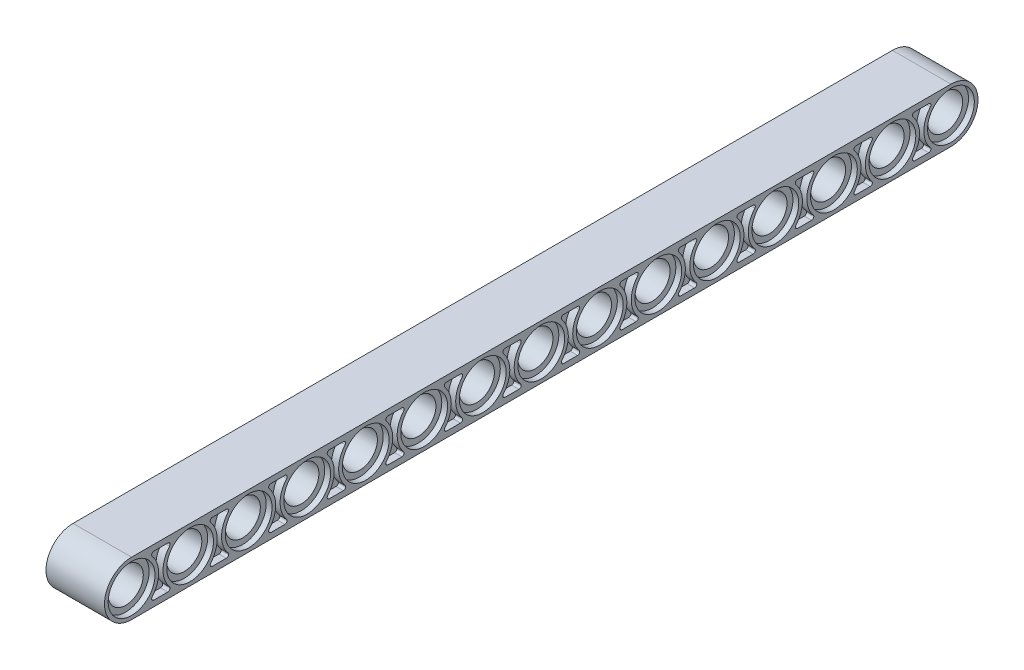
SolidWorks part; units mm, degrees
ref_plane "Front Plane" through (0, 0, 0) normal (0, 0, 1) x (1, 0, 0)
ref_plane "Top Plane" through (0, 0, 0) normal (0, 1, 0) x (1, 0, 0)
ref_plane "Right Plane" through (0, 0, 0) normal (1, 0, 0) x (0, 0, -1)
sketch "Sketch1" plane through (0, 0, 0) normal (1, 0, 0) x (0, 0, -1)
  line L0 (-29.185, 0) -> (82.815, 0) construction
  line L1 (-29.185, 3.7) -> (82.815, 3.7)
  line L2 (-29.185, -3.7) -> (82.815, -3.7)
  arc A0 (-29.185, 3.7) -> (-29.185, -3.7) centre (-29.185, 0) ccw
  arc A1 (82.815, -3.7) -> (82.815, 3.7) centre (82.815, 0) ccw
  circle A2 centre (-29.185, 0) radius 2.4
  circle A3 centre (-21.185, 0) radius 2.4
  circle A4 centre (-13.185, 0) radius 2.4
  circle A5 centre (-5.185, 0) radius 2.4
  circle A6 centre (2.815, 0) radius 2.4
  circle A7 centre (10.815, 0) radius 2.4
  circle A8 centre (18.815, 0) radius 2.4
  circle A9 centre (26.815, 0) radius 2.4
  circle A10 centre (34.815, 0) radius 2.4
  circle A11 centre (42.815, 0) radius 2.4
  circle A12 centre (50.815, 0) radius 2.4
  circle A13 centre (58.815, 0) radius 2.4
  circle A14 centre (66.815, 0) radius 2.4
  circle A15 centre (74.815, 0) radius 2.4
  circle A16 centre (82.815, 0) radius 2.4
  point P3 (26.815, 0)
  dimension "D3" = 15
  dimension "D1" = 7.4
  dimension "D2" = 112
extrude "Boss-Extrude1" add sketch "Sketch1" along normal blind 8
sketch "Sketch2" plane through (8, 0, 0) normal (1, 0, 0) x (0, 0, -1)
  line L0 (-26.1453, 2.9) -> (-24.2248, 2.9)
  line L1 (82.815, 3.7) -> (-29.185, 3.7) construction
  line L2 (-29.185, 0) -> (-21.185, 0) construction
  line L3 (-26.1453, -2.9) -> (-24.2248, -2.9)
  line L4 (-18.1453, 2.9) -> (-16.2248, 2.9)
  line L5 (-18.1453, -2.9) -> (-16.2248, -2.9)
  line L6 (-21.185, 0) -> (-13.185, 0) construction
  line L7 (-10.1453, 2.9) -> (-8.2248, 2.9)
  line L8 (-10.1453, -2.9) -> (-8.2248, -2.9)
  line L9 (-13.185, 0) -> (-5.185, 0) construction
  line L10 (-2.1453, 2.9) -> (-0.2248, 2.9)
  line L11 (-2.1453, -2.9) -> (-0.2248, -2.9)
  line L12 (-5.185, 0) -> (2.815, 0) construction
  line L13 (5.8547, 2.9) -> (7.7752, 2.9)
  line L14 (5.8547, -2.9) -> (7.7752, -2.9)
  line L15 (2.815, 0) -> (10.815, 0) construction
  line L16 (13.8547, 2.9) -> (15.7752, 2.9)
  line L17 (13.8547, -2.9) -> (15.7752, -2.9)
  line L18 (10.815, 0) -> (18.815, 0) construction
  line L19 (21.8547, 2.9) -> (23.7752, 2.9)
  line L20 (21.8547, -2.9) -> (23.7752, -2.9)
  line L21 (18.815, 0) -> (26.815, 0) construction
  line L22 (29.8547, 2.9) -> (31.7752, 2.9)
  line L23 (29.8547, -2.9) -> (31.7752, -2.9)
  line L24 (26.815, 0) -> (34.815, 0) construction
  line L25 (37.8547, 2.9) -> (39.7752, 2.9)
  line L26 (37.8547, -2.9) -> (39.7752, -2.9)
  line L27 (34.815, 0) -> (42.815, 0) construction
  line L28 (45.8547, 2.9) -> (47.7752, 2.9)
  line L29 (45.8547, -2.9) -> (47.7752, -2.9)
  line L30 (42.815, 0) -> (50.815, 0) construction
  line L31 (53.8547, 2.9) -> (55.7752, 2.9)
  line L32 (53.8547, -2.9) -> (55.7752, -2.9)
  line L33 (50.815, 0) -> (58.815, 0) construction
  line L34 (61.8547, 2.9) -> (63.7752, 2.9)
  line L35 (61.8547, -2.9) -> (63.7752, -2.9)
  line L36 (58.815, 0) -> (66.815, 0) construction
  line L37 (69.8547, 2.9) -> (71.7752, 2.9)
  line L38 (69.8547, -2.9) -> (71.7752, -2.9)
  line L39 (66.815, 0) -> (74.815, 0) construction
  line L40 (77.8547, 2.9) -> (79.7752, 2.9)
  line L41 (77.8547, -2.9) -> (79.7752, -2.9)
  line L42 (74.815, 0) -> (82.815, 0) construction
  arc A0 (-26.3733, -2.405) -> (-26.3733, 2.405) centre (-29.185, 0) ccw
  arc A1 (-23.9968, 2.405) -> (-23.9968, -2.405) centre (-21.185, 0) ccw
  arc A2 (-26.3733, -2.405) -> (-26.1453, -2.9) centre (-26.1453, -2.6) ccw
  arc A3 (-23.9968, -2.405) -> (-24.2248, -2.9) centre (-24.2248, -2.6) cw
  arc A4 (-23.9968, 2.405) -> (-24.2248, 2.9) centre (-24.2248, 2.6) ccw
  arc A5 (-26.3733, 2.405) -> (-26.1453, 2.9) centre (-26.1453, 2.6) cw
  arc A6 (-18.3733, -2.405) -> (-18.3733, 2.405) centre (-21.185, 0) ccw
  arc A7 (-15.9968, 2.405) -> (-15.9968, -2.405) centre (-13.185, 0) ccw
  arc A8 (-18.3733, -2.405) -> (-18.1453, -2.9) centre (-18.1453, -2.6) ccw
  arc A9 (-15.9968, -2.405) -> (-16.2248, -2.9) centre (-16.2248, -2.6) cw
  arc A10 (-15.9968, 2.405) -> (-16.2248, 2.9) centre (-16.2248, 2.6) ccw
  arc A11 (-18.3733, 2.405) -> (-18.1453, 2.9) centre (-18.1453, 2.6) cw
  arc A12 (-10.3733, -2.405) -> (-10.3733, 2.405) centre (-13.185, 0) ccw
  arc A13 (-7.9968, 2.405) -> (-7.9968, -2.405) centre (-5.185, 0) ccw
  arc A14 (-10.3733, -2.405) -> (-10.1453, -2.9) centre (-10.1453, -2.6) ccw
  arc A15 (-7.9968, -2.405) -> (-8.2248, -2.9) centre (-8.2248, -2.6) cw
  arc A16 (-7.9968, 2.405) -> (-8.2248, 2.9) centre (-8.2248, 2.6) ccw
  arc A17 (-10.3733, 2.405) -> (-10.1453, 2.9) centre (-10.1453, 2.6) cw
  arc A18 (-2.3733, -2.405) -> (-2.3733, 2.405) centre (-5.185, 0) ccw
  arc A19 (0.0032, 2.405) -> (0.0032, -2.405) centre (2.815, 0) ccw
  arc A20 (-2.3733, -2.405) -> (-2.1453, -2.9) centre (-2.1453, -2.6) ccw
  arc A21 (0.0032, -2.405) -> (-0.2248, -2.9) centre (-0.2248, -2.6) cw
  arc A22 (0.0032, 2.405) -> (-0.2248, 2.9) centre (-0.2248, 2.6) ccw
  arc A23 (-2.3733, 2.405) -> (-2.1453, 2.9) centre (-2.1453, 2.6) cw
  arc A24 (5.6267, -2.405) -> (5.6267, 2.405) centre (2.815, 0) ccw
  arc A25 (8.0032, 2.405) -> (8.0032, -2.405) centre (10.815, 0) ccw
  arc A26 (5.6267, -2.405) -> (5.8547, -2.9) centre (5.8547, -2.6) ccw
  arc A27 (8.0032, -2.405) -> (7.7752, -2.9) centre (7.7752, -2.6) cw
  arc A28 (8.0032, 2.405) -> (7.7752, 2.9) centre (7.7752, 2.6) ccw
  arc A29 (5.6267, 2.405) -> (5.8547, 2.9) centre (5.8547, 2.6) cw
  arc A30 (13.6267, -2.405) -> (13.6267, 2.405) centre (10.815, 0) ccw
  arc A31 (16.0032, 2.405) -> (16.0032, -2.405) centre (18.815, 0) ccw
  arc A32 (13.6267, -2.405) -> (13.8547, -2.9) centre (13.8547, -2.6) ccw
  arc A33 (16.0032, -2.405) -> (15.7752, -2.9) centre (15.7752, -2.6) cw
  arc A34 (16.0032, 2.405) -> (15.7752, 2.9) centre (15.7752, 2.6) ccw
  arc A35 (13.6267, 2.405) -> (13.8547, 2.9) centre (13.8547, 2.6) cw
  arc A36 (21.6267, -2.405) -> (21.6267, 2.405) centre (18.815, 0) ccw
  arc A37 (24.0032, 2.405) -> (24.0032, -2.405) centre (26.815, 0) ccw
  arc A38 (21.6267, -2.405) -> (21.8547, -2.9) centre (21.8547, -2.6) ccw
  arc A39 (24.0032, -2.405) -> (23.7752, -2.9) centre (23.7752, -2.6) cw
  arc A40 (24.0032, 2.405) -> (23.7752, 2.9) centre (23.7752, 2.6) ccw
  arc A41 (21.6267, 2.405) -> (21.8547, 2.9) centre (21.8547, 2.6) cw
  arc A42 (29.6267, -2.405) -> (29.6267, 2.405) centre (26.815, 0) ccw
  arc A43 (32.0032, 2.405) -> (32.0032, -2.405) centre (34.815, 0) ccw
  arc A44 (29.6267, -2.405) -> (29.8547, -2.9) centre (29.8547, -2.6) ccw
  arc A45 (32.0032, -2.405) -> (31.7752, -2.9) centre (31.7752, -2.6) cw
  arc A46 (32.0032, 2.405) -> (31.7752, 2.9) centre (31.7752, 2.6) ccw
  arc A47 (29.6267, 2.405) -> (29.8547, 2.9) centre (29.8547, 2.6) cw
  arc A48 (37.6267, -2.405) -> (37.6267, 2.405) centre (34.815, 0) ccw
  arc A49 (40.0032, 2.405) -> (40.0032, -2.405) centre (42.815, 0) ccw
  arc A50 (37.6267, -2.405) -> (37.8547, -2.9) centre (37.8547, -2.6) ccw
  arc A51 (40.0032, -2.405) -> (39.7752, -2.9) centre (39.7752, -2.6) cw
  arc A52 (40.0032, 2.405) -> (39.7752, 2.9) centre (39.7752, 2.6) ccw
  arc A53 (37.6267, 2.405) -> (37.8547, 2.9) centre (37.8547, 2.6) cw
  arc A54 (45.6267, -2.405) -> (45.6267, 2.405) centre (42.815, 0) ccw
  arc A55 (48.0032, 2.405) -> (48.0032, -2.405) centre (50.815, 0) ccw
  arc A56 (45.6267, -2.405) -> (45.8547, -2.9) centre (45.8547, -2.6) ccw
  arc A57 (48.0032, -2.405) -> (47.7752, -2.9) centre (47.7752, -2.6) cw
  arc A58 (48.0032, 2.405) -> (47.7752, 2.9) centre (47.7752, 2.6) ccw
  arc A59 (45.6267, 2.405) -> (45.8547, 2.9) centre (45.8547, 2.6) cw
  arc A60 (53.6267, -2.405) -> (53.6267, 2.405) centre (50.815, 0) ccw
  arc A61 (56.0032, 2.405) -> (56.0032, -2.405) centre (58.815, 0) ccw
  arc A62 (53.6267, -2.405) -> (53.8547, -2.9) centre (53.8547, -2.6) ccw
  arc A63 (56.0032, -2.405) -> (55.7752, -2.9) centre (55.7752, -2.6) cw
  arc A64 (56.0032, 2.405) -> (55.7752, 2.9) centre (55.7752, 2.6) ccw
  arc A65 (53.6267, 2.405) -> (53.8547, 2.9) centre (53.8547, 2.6) cw
  arc A66 (61.6267, -2.405) -> (61.6267, 2.405) centre (58.815, 0) ccw
  arc A67 (64.0032, 2.405) -> (64.0032, -2.405) centre (66.815, 0) ccw
  arc A68 (61.6267, -2.405) -> (61.8547, -2.9) centre (61.8547, -2.6) ccw
  arc A69 (64.0032, -2.405) -> (63.7752, -2.9) centre (63.7752, -2.6) cw
  arc A70 (64.0032, 2.405) -> (63.7752, 2.9) centre (63.7752, 2.6) ccw
  arc A71 (61.6267, 2.405) -> (61.8547, 2.9) centre (61.8547, 2.6) cw
  arc A72 (69.6267, -2.405) -> (69.6267, 2.405) centre (66.815, 0) ccw
  arc A73 (72.0032, 2.405) -> (72.0032, -2.405) centre (74.815, 0) ccw
  arc A74 (69.6267, -2.405) -> (69.8547, -2.9) centre (69.8547, -2.6) ccw
  arc A75 (72.0032, -2.405) -> (71.7752, -2.9) centre (71.7752, -2.6) cw
  arc A76 (72.0032, 2.405) -> (71.7752, 2.9) centre (71.7752, 2.6) ccw
  arc A77 (69.6267, 2.405) -> (69.8547, 2.9) centre (69.8547, 2.6) cw
  arc A78 (77.6267, -2.405) -> (77.6267, 2.405) centre (74.815, 0) ccw
  arc A79 (80.0032, 2.405) -> (80.0032, -2.405) centre (82.815, 0) ccw
  arc A80 (77.6267, -2.405) -> (77.8547, -2.9) centre (77.8547, -2.6) ccw
  arc A81 (80.0032, -2.405) -> (79.7752, -2.9) centre (79.7752, -2.6) cw
  arc A82 (80.0032, 2.405) -> (79.7752, 2.9) centre (79.7752, 2.6) ccw
  arc A83 (77.6267, 2.405) -> (77.8547, 2.9) centre (77.8547, 2.6) cw
  dimension "D3" = 0.3
  dimension "D2" = 0.8
  dimension "D1" = 2
  dimension "D4" = 14
extrude "Cut-Extrude1" cut sketch "Sketch2" against normal blind 1
sketch "Sketch3" plane through (8, 0, 0) normal (1, 0, 0) x (0, 0, -1)
  circle A0 centre (-29.185, 0) radius 3.2
  circle A1 centre (-21.185, 0) radius 3.2
  circle A2 centre (-13.185, 0) radius 3.2
  circle A3 centre (-5.185, 0) radius 3.2
  circle A4 centre (2.815, 0) radius 3.2
  circle A5 centre (10.815, 0) radius 3.2
  circle A6 centre (18.815, 0) radius 3.2
  circle A7 centre (26.815, 0) radius 3.2
  circle A8 centre (34.815, 0) radius 3.2
  circle A9 centre (42.815, 0) radius 3.2
  circle A10 centre (50.815, 0) radius 3.2
  circle A11 centre (58.815, 0) radius 3.2
  circle A12 centre (66.815, 0) radius 3.2
  circle A13 centre (74.815, 0) radius 3.2
  circle A14 centre (82.815, 0) radius 3.2
  dimension "D1" = 15
extrude "Cut-Extrude2" cut sketch "Sketch3" against normal blind 0.8
ref_plane "Plane1" through (4, 0, 0) normal (1, 0, 0) x (0, 0, -1)
mirror "Mirror1" about plane through (4, 0, 0) normal (1, 0, 0) of "Cut-Extrude1", "Cut-Extrude2"
